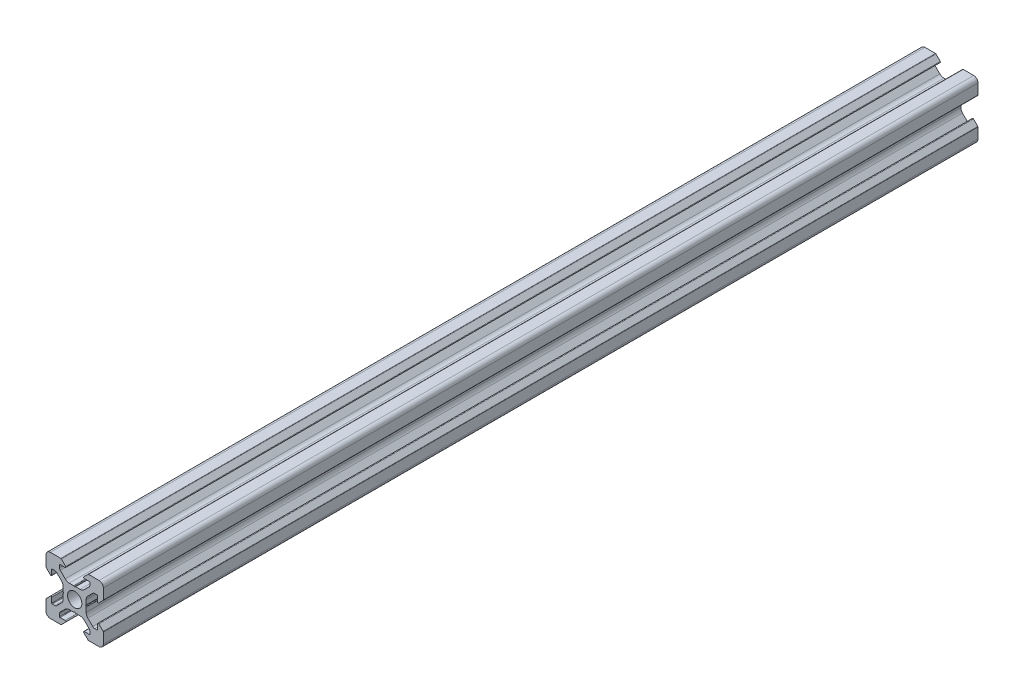
SolidWorks part; units mm, degrees
ref_plane "Спереди" through (0, 0, 0) normal (0, 0, 1) x (1, 0, 0)
ref_plane "Сверху" through (0, 0, 0) normal (0, 1, 0) x (1, 0, 0)
ref_plane "Справа" through (0, 0, 0) normal (1, 0, 0) x (0, 0, -1)
sketch "Model" plane through (0, 0, 0) normal (0, 0, 1) x (1, 0, 0)
  line L0 (18.9421, 33.3622) -> (18.9421, 34.9233)
  line L1 (18.3564, 36.3375) -> (16.6623, 38.0316)
  line L2 (15.9551, 38.3245) -> (15.1421, 38.3245)
  line L3 (14.9421, 38.1245) -> (14.9421, 36.3545)
  line L4 (13.0154, 37.6777) -> (14.5154, 36.1777)
  line L5 (12.9421, 37.8545) -> (12.9421, 41.5245)
  line L6 (18.2889, 42.9513) -> (19.7889, 41.4513)
  line L7 (22.7606, 36.9697) -> (22.9421, 36.8245)
  line L8 (23.1237, 36.9697) -> (22.9421, 36.8245)
  line L9 (23.2798, 37.0245) -> (24.8409, 37.0245)
  line L10 (26.2551, 37.6103) -> (27.9493, 39.3044)
  line L11 (28.2421, 40.0115) -> (28.2421, 40.8245)
  line L12 (28.0421, 41.0245) -> (26.2721, 41.0245)
  line L13 (27.5954, 42.9513) -> (26.0954, 41.4513)
  line L14 (27.7721, 43.0245) -> (31.4421, 43.0245)
  line L15 (32.9421, 37.8545) -> (32.9421, 41.5245)
  line L16 (32.8689, 37.6777) -> (31.3689, 36.1777)
  line L17 (30.9421, 38.1245) -> (30.9421, 36.3545)
  line L18 (29.9292, 38.3245) -> (30.7421, 38.3245)
  line L19 (27.5279, 36.3375) -> (29.222, 38.0316)
  line L20 (26.9421, 33.3622) -> (26.9421, 34.9233)
  line L21 (26.8874, 33.206) -> (26.7421, 33.0245)
  line L22 (26.8874, 32.843) -> (26.7421, 33.0245)
  line L23 (26.9421, 32.6868) -> (26.9421, 31.1257)
  line L24 (27.5279, 29.7115) -> (29.222, 28.0174)
  line L25 (29.9292, 27.7245) -> (30.7421, 27.7245)
  line L26 (30.9421, 27.9245) -> (30.9421, 29.6945)
  line L27 (32.8689, 28.3713) -> (31.3689, 29.8713)
  line L28 (32.9421, 28.1945) -> (32.9421, 24.5245)
  line L29 (27.7721, 23.0245) -> (31.4421, 23.0245)
  line L30 (27.5954, 23.0977) -> (26.0954, 24.5977)
  line L31 (28.0421, 25.0245) -> (26.2721, 25.0245)
  line L32 (28.2421, 26.0375) -> (28.2421, 25.2245)
  line L33 (26.2551, 28.4387) -> (27.9493, 26.7446)
  line L34 (23.2798, 29.0245) -> (24.8409, 29.0245)
  line L35 (23.1237, 29.0793) -> (22.9421, 29.2245)
  line L36 (22.7606, 29.0793) -> (22.9421, 29.2245)
  line L37 (19.6292, 28.4387) -> (17.935, 26.7446)
  line L38 (17.6421, 26.0375) -> (17.6421, 25.2245)
  line L39 (17.8421, 25.0245) -> (19.6121, 25.0245)
  line L40 (18.2889, 23.0977) -> (19.7889, 24.5977)
  line L41 (18.1121, 23.0245) -> (14.4421, 23.0245)
  line L42 (12.9421, 28.1945) -> (12.9421, 24.5245)
  line L43 (13.0154, 28.3713) -> (14.5154, 29.8713)
  line L44 (14.9421, 27.9245) -> (14.9421, 29.6945)
  line L45 (15.9551, 27.7245) -> (15.1421, 27.7245)
  line L46 (18.3564, 29.7115) -> (16.6623, 28.0174)
  line L47 (18.9421, 32.6868) -> (18.9421, 31.1257)
  line L48 (18.9969, 32.843) -> (19.1421, 33.0245)
  line L49 (18.9969, 33.206) -> (19.1421, 33.0245)
  line L50 (22.6045, 29.0245) -> (21.0434, 29.0245)
  line L51 (22.6045, 37.0245) -> (21.0434, 37.0245)
  line L52 (19.6292, 37.6103) -> (17.935, 39.3044)
  line L53 (17.6421, 40.0115) -> (17.6421, 40.8245)
  line L54 (17.8421, 41.0245) -> (19.6121, 41.0245)
  line L55 (18.1121, 43.0245) -> (14.4421, 43.0245)
  arc A0 (18.9421, 33.3622) -> (18.9969, 33.206) centre (19.1921, 33.3622) ccw
  arc A1 (18.9421, 34.9233) -> (18.3564, 36.3375) centre (16.9421, 34.9233) ccw
  arc A2 (16.6623, 38.0316) -> (15.9551, 38.3245) centre (15.9551, 37.3245) ccw
  arc A3 (15.1421, 38.3245) -> (14.9421, 38.1245) centre (15.1421, 38.1245) ccw
  arc A4 (14.5154, 36.1777) -> (14.9421, 36.3545) centre (14.6921, 36.3545) ccw
  arc A5 (12.9421, 37.8545) -> (13.0154, 37.6777) centre (13.1921, 37.8545) ccw
  arc A6 (14.4421, 43.0245) -> (12.9421, 41.5245) centre (14.4421, 41.5245) ccw
  arc A7 (18.2889, 42.9513) -> (18.1121, 43.0245) centre (18.1121, 42.7745) ccw
  arc A8 (19.6121, 41.0245) -> (19.7889, 41.4513) centre (19.6121, 41.2745) ccw
  arc A9 (17.8421, 41.0245) -> (17.6421, 40.8245) centre (17.8421, 40.8245) ccw
  arc A10 (17.6421, 40.0115) -> (17.935, 39.3044) centre (18.6421, 40.0115) ccw
  arc A11 (19.6292, 37.6103) -> (21.0434, 37.0245) centre (21.0434, 39.0245) ccw
  arc A12 (22.7606, 36.9697) -> (22.6045, 37.0245) centre (22.6045, 36.7745) ccw
  arc A13 (23.2798, 37.0245) -> (23.1237, 36.9697) centre (23.2798, 36.7745) ccw
  arc A14 (24.8409, 37.0245) -> (26.2551, 37.6103) centre (24.8409, 39.0245) ccw
  arc A15 (27.9493, 39.3044) -> (28.2421, 40.0115) centre (27.2421, 40.0115) ccw
  arc A16 (28.2421, 40.8245) -> (28.0421, 41.0245) centre (28.0421, 40.8245) ccw
  arc A17 (26.0954, 41.4513) -> (26.2721, 41.0245) centre (26.2721, 41.2745) ccw
  arc A18 (27.7721, 43.0245) -> (27.5954, 42.9513) centre (27.7721, 42.7745) ccw
  arc A19 (32.9421, 41.5245) -> (31.4421, 43.0245) centre (31.4421, 41.5245) ccw
  arc A20 (32.8689, 37.6777) -> (32.9421, 37.8545) centre (32.6921, 37.8545) ccw
  arc A21 (30.9421, 36.3545) -> (31.3689, 36.1777) centre (31.1921, 36.3545) ccw
  arc A22 (30.9421, 38.1245) -> (30.7421, 38.3245) centre (30.7421, 38.1245) ccw
  arc A23 (29.9292, 38.3245) -> (29.222, 38.0316) centre (29.9292, 37.3245) ccw
  arc A24 (27.5279, 36.3375) -> (26.9421, 34.9233) centre (28.9421, 34.9233) ccw
  arc A25 (26.8874, 33.206) -> (26.9421, 33.3622) centre (26.6921, 33.3622) ccw
  arc A26 (26.9421, 32.6868) -> (26.8874, 32.843) centre (26.6921, 32.6868) ccw
  arc A27 (26.9421, 31.1257) -> (27.5279, 29.7115) centre (28.9421, 31.1257) ccw
  arc A28 (29.222, 28.0174) -> (29.9292, 27.7245) centre (29.9292, 28.7245) ccw
  arc A29 (30.7421, 27.7245) -> (30.9421, 27.9245) centre (30.7421, 27.9245) ccw
  arc A30 (31.3689, 29.8713) -> (30.9421, 29.6945) centre (31.1921, 29.6945) ccw
  arc A31 (32.9421, 28.1945) -> (32.8689, 28.3713) centre (32.6921, 28.1945) ccw
  arc A32 (31.4421, 23.0245) -> (32.9421, 24.5245) centre (31.4421, 24.5245) ccw
  arc A33 (27.5954, 23.0977) -> (27.7721, 23.0245) centre (27.7721, 23.2745) ccw
  arc A34 (26.2721, 25.0245) -> (26.0954, 24.5977) centre (26.2721, 24.7745) ccw
  arc A35 (28.0421, 25.0245) -> (28.2421, 25.2245) centre (28.0421, 25.2245) ccw
  arc A36 (28.2421, 26.0375) -> (27.9493, 26.7446) centre (27.2421, 26.0375) ccw
  arc A37 (26.2551, 28.4387) -> (24.8409, 29.0245) centre (24.8409, 27.0245) ccw
  arc A38 (23.1237, 29.0793) -> (23.2798, 29.0245) centre (23.2798, 29.2745) ccw
  arc A39 (22.6045, 29.0245) -> (22.7606, 29.0793) centre (22.6045, 29.2745) ccw
  arc A40 (21.0434, 29.0245) -> (19.6292, 28.4387) centre (21.0434, 27.0245) ccw
  arc A41 (17.935, 26.7446) -> (17.6421, 26.0375) centre (18.6421, 26.0375) ccw
  arc A42 (17.6421, 25.2245) -> (17.8421, 25.0245) centre (17.8421, 25.2245) ccw
  arc A43 (19.7889, 24.5977) -> (19.6121, 25.0245) centre (19.6121, 24.7745) ccw
  arc A44 (18.1121, 23.0245) -> (18.2889, 23.0977) centre (18.1121, 23.2745) ccw
  arc A45 (12.9421, 24.5245) -> (14.4421, 23.0245) centre (14.4421, 24.5245) ccw
  arc A46 (13.0154, 28.3713) -> (12.9421, 28.1945) centre (13.1921, 28.1945) ccw
  arc A47 (14.9421, 29.6945) -> (14.5154, 29.8713) centre (14.6921, 29.6945) ccw
  arc A48 (14.9421, 27.9245) -> (15.1421, 27.7245) centre (15.1421, 27.9245) ccw
  arc A49 (15.9551, 27.7245) -> (16.6623, 28.0174) centre (15.9551, 28.7245) ccw
  arc A50 (18.3564, 29.7115) -> (18.9421, 31.1257) centre (16.9421, 31.1257) ccw
  arc A51 (18.9969, 32.843) -> (18.9421, 32.6868) centre (19.1921, 32.6868) ccw
  circle A52 centre (22.9421, 33.0245) radius 2.5
extrude "Бобышка-Вытянуть1" add sketch "Model" along normal blind 305
